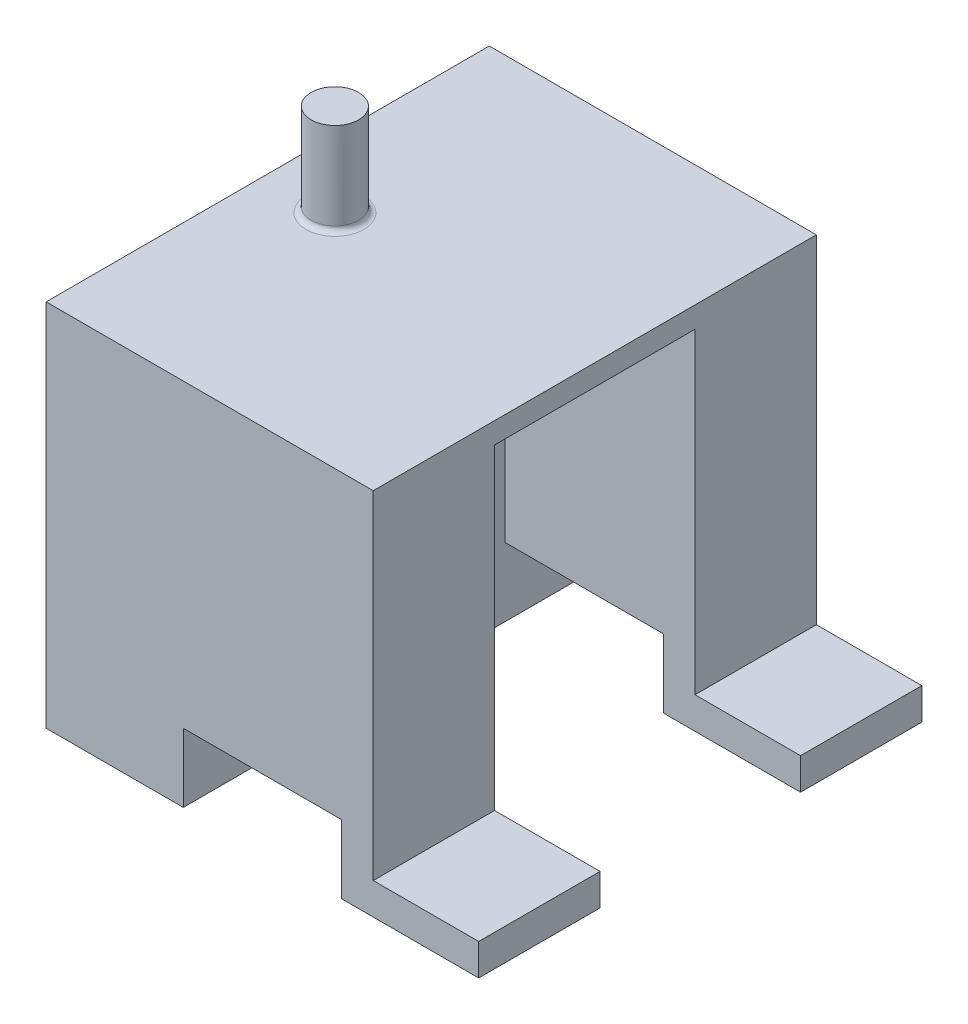
SolidWorks part; units mm, degrees
ref_plane "Front Plane" through (0, 0, 0) normal (0, 0, 1) x (1, 0, 0)
ref_plane "Top Plane" through (0, 0, 0) normal (0, 1, 0) x (1, 0, 0)
ref_plane "Right Plane" through (0, 0, 0) normal (1, 0, 0) x (0, 0, -1)
sketch "Sketch1" plane through (0, 0, 0) normal (0, 0, 1) x (1, 0, 0)
  line L1 (19.5806, 0) -> (19.5806, 6.5)
  line L2 (19.5806, 6.5) -> (4.5806, 6.5)
  line L3 (4.5806, 6.5) -> (4.5806, 0)
  line L4 (4.5806, 0) -> (-8.4194, 0)
  line L5 (-8.4194, 0) -> (-8.4194, 3)
  line L8 (1.5806, 35) -> (22.5806, 35)
  line L11 (22.5806, 35) -> (22.5806, 3)
  line L12 (19.5806, 0) -> (32.5806, 0)
  line L13 (32.5806, 0) -> (32.5806, 3)
  line L14 (32.5806, 3) -> (22.5806, 3)
  line L15 (-8.4194, 3) -> (-8.4194, 35)
  line L16 (-8.4194, 35) -> (1.5806, 35)
  dimension "D1" = 6.5
  dimension "D2" = 35
  dimension "D3" = 3
  dimension "D4" = 3
  dimension "D7" = 15
  dimension "D8" = 10
extrude "Boss-Extrude1" add sketch "Sketch1" along normal blind 42
sketch "Sketch2" plane through (32.5806, 0, 0) normal (1, 0, 0) x (0, 0, -1)
  line L0 (-42, 0) -> (0, 0) construction
  line L1 (-11.5, 0) -> (-30.5, 0)
  line L2 (-11.5, 0) -> (-11.5, 33)
  line L3 (-11.5, 33) -> (-30.5, 33)
  line L4 (-30.5, 0) -> (-30.5, 33)
  line L5 (0, 19) -> (-42, 19) construction
  line L6 (0, 3) -> (0, 35) construction
  line L7 (-42, 3) -> (-42, 35) construction
  line L8 (-42, 19) -> (-42, 35) construction
  line L9 (-42, 35) -> (0, 0) construction
  line L10 (0, 0) -> (0, 35) construction
  line L11 (0, 35) -> (-42, 0) construction
  line L12 (-21, 17.5) -> (-21, 0) construction
  point P12 (-21, 0)
  dimension "D1" = 33
  dimension "D2" = 19
extrude "Cut-Extrude1" cut sketch "Sketch2" against normal up to surface (28 mm away) up to face at (4.5806, 3.25, 21)
ref_plane "Plane1" through (0, 0, 21) normal (0, 0, -1) x (-1, 0, 0)
sketch "Sketch3" plane through (0, 35, 0) normal (0, 1, 0) x (1, 0, 0)
  line L0 (19.25, -21) -> (-19.25, -21) construction
  circle A0 centre (-2.0517, -21) radius 2.25
  dimension "D1" = 4.5
extrude "Boss-Extrude2" add sketch "Sketch3" along normal blind 8.75 contours A0
sketch "Sketch4" plane through (0, 43.75, 0) normal (0, 1, 0) x (1, 0, 0)
  circle A0 centre (-2.0517, -21) radius 2.25
  dimension "D1" = 4.5
fillet "Fillet1" radius 0.5 1 edges at (-2.0517, 35, 18.75)
